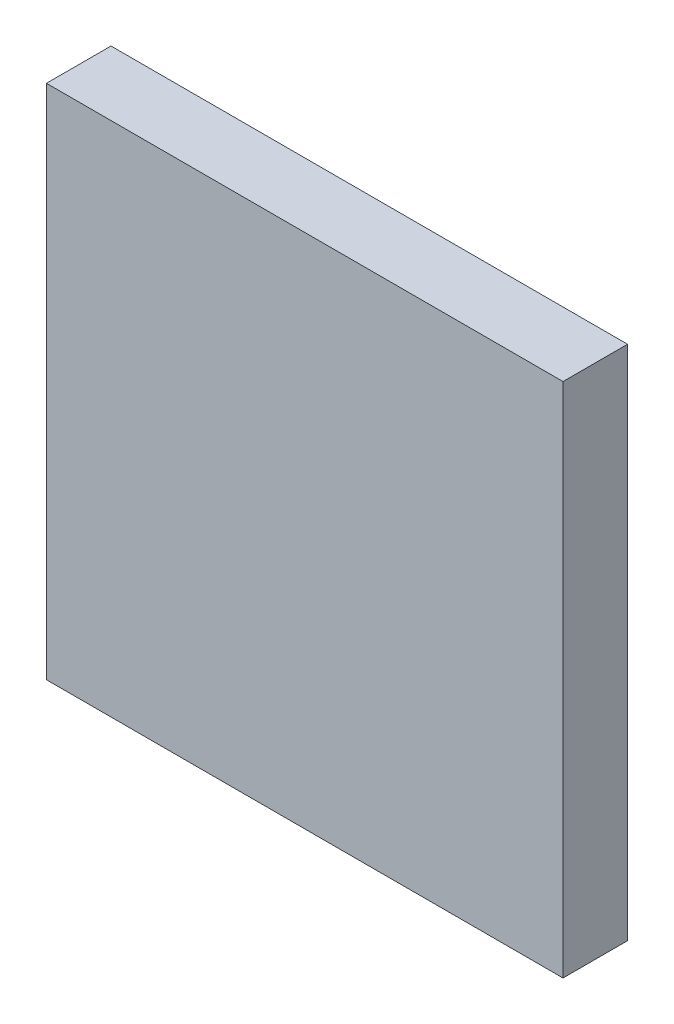
SolidWorks part; units mm, degrees
material "6061 Alloy"
ref_plane "Front Plane" through (0, 0, 0) normal (0, 0, 1) x (1, 0, 0)
ref_plane "Top Plane" through (0, 0, 0) normal (0, 1, 0) x (1, 0, 0)
ref_plane "Right Plane" through (0, 0, 0) normal (1, 0, 0) x (0, 0, -1)
sketch "Sketch1" plane through (0, 0, 0) normal (0, 0, 1) x (1, 0, 0)
  line L1 (-43.2837, -26.6311) -> (-17.8837, -26.6311)
  line L2 (-43.2837, -26.6311) -> (-43.2837, -1.2311)
  line L3 (-43.2837, -1.2311) -> (-17.8837, -1.2311)
  line L4 (-17.8837, -26.6311) -> (-17.8837, -1.2311)
  dimension "D1" = 25.4
  dimension "D2" = 25.4
extrude "Boss-Extrude1" add sketch "Sketch1" along normal blind 3.175
